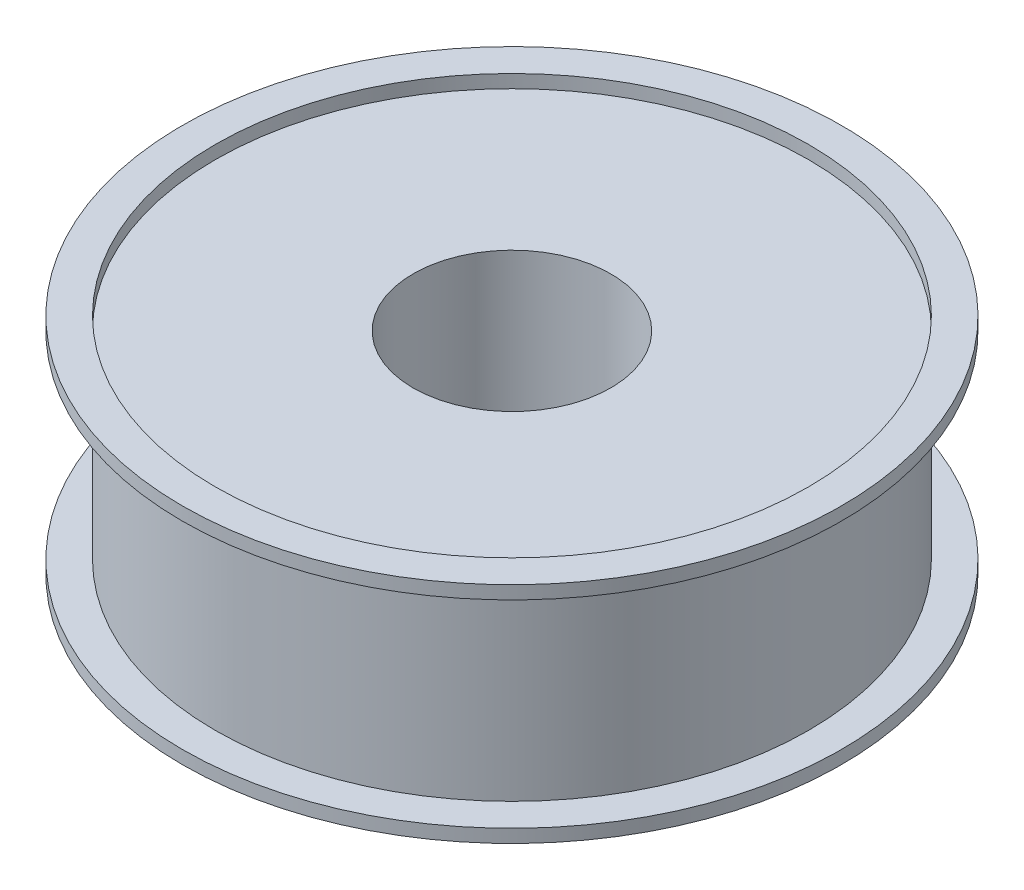
SolidWorks part; units mm, degrees
ref_plane "Front Plane" through (0, 0, 0) normal (0, 0, 1) x (1, 0, 0)
ref_plane "Top Plane" through (0, 0, 0) normal (0, 1, 0) x (1, 0, 0)
ref_plane "Right Plane" through (0, 0, 0) normal (1, 0, 0) x (0, 0, -1)
sketch "Sketch1" plane through (0, 0, 0) normal (0, 1, 0) x (1, 0, 0)
  circle A0 centre (0, 0) radius 100
  circle A2 centre (0, 0) radius 90
extrude "Boss-Extrude1" add sketch "Sketch1" along normal blind 4 contours A0 A2
sketch "Sketch2" plane through (0, 4, 0) normal (0, 1, 0) x (1, 0, 0)
  circle A0 centre (0, 0) radius 30
  circle A1 centre (0, 0) radius 90
extrude "Boss-Extrude2" add sketch "Sketch2" along normal blind 60 separate body
sketch "Sketch3" plane through (0, 64, 0) normal (0, 1, 0) x (1, 0, 0)
  circle A0 centre (0, 0) radius 100
  circle A1 centre (0, 0) radius 30
extrude "Boss-Extrude3" add sketch "Sketch3" along normal blind 4
sketch "Sketch4" plane through (0, 68, 0) normal (0, 1, 0) x (1, 0, 0)
  circle A0 centre (0, 0) radius 90
extrude "Cut-Extrude1" cut sketch "Sketch4" against normal blind 4
